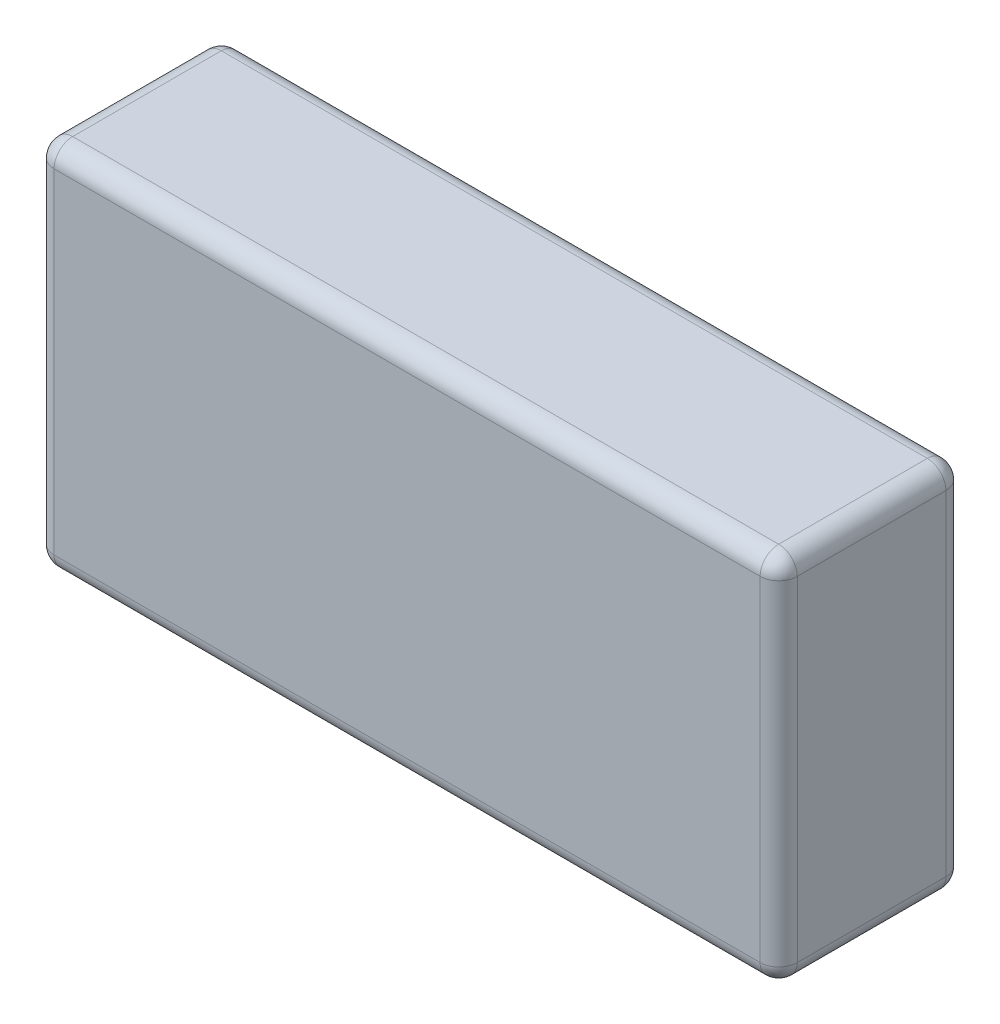
SolidWorks part; units mm, degrees
ref_plane "Plano frontal" through (0, 0, 0) normal (0, 0, 1) x (1, 0, 0)
ref_plane "Plano superior" through (0, 0, 0) normal (0, 1, 0) x (1, 0, 0)
ref_plane "Plano direito" through (0, 0, 0) normal (1, 0, 0) x (0, 0, -1)
sketch "Esboço1" plane through (0, 0, 0) normal (0, 1, 0) x (1, 0, 0)
  line L1 (-54.052, 23.4295) -> (145.948, 23.4295)
  line L2 (-54.052, 23.4295) -> (-54.052, -26.5705)
  line L3 (-54.052, -26.5705) -> (145.948, -26.5705)
  line L4 (145.948, 23.4295) -> (145.948, -26.5705)
extrude "Ressalto-extrusão1" add sketch "Esboço1" along normal blind 100
fillet "Filete8" radius 5 12 edges at (-54.052, 100, 1.5705) (-54.052, 0, 1.5705) (-54.052, 50, 26.5705) (45.948, 100, 26.5705) (45.948, 0, 26.5705) (145.948, 50, 26.5705) (145.948, 100, 1.5705) (145.948, 0, 1.5705) (145.948, 50, -23.4295) (45.948, 100, -23.4295) (-54.052, 50, -23.4295) (45.948, 0, -23.4295)
